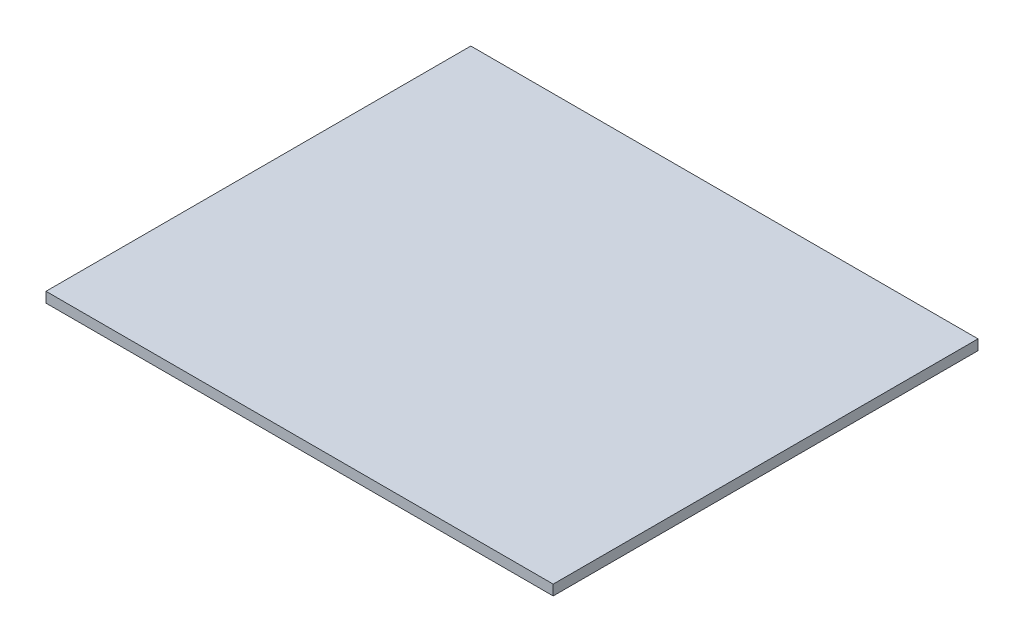
SolidWorks part; units mm, degrees
ref_plane "Front Plane" through (0, 0, 0) normal (0, 0, 1) x (1, 0, 0)
ref_plane "Top Plane" through (0, 0, 0) normal (0, 1, 0) x (1, 0, 0)
ref_plane "Right Plane" through (0, 0, 0) normal (1, 0, 0) x (0, 0, -1)
sketch "Sketch1" plane through (0, 0, 0) normal (0, 1, 0) x (1, 0, 0)
  line L1 (0, -523.875) -> (625.475, -523.875)
  line L2 (0, -523.875) -> (0, 0)
  line L3 (0, 0) -> (625.475, 0)
  line L4 (625.475, -523.875) -> (625.475, 0)
  line L5 (0, -523.875) -> (625.475, 0) construction
  line L6 (0, 0) -> (625.475, -523.875) construction
  point P0 (-2.6304, 18.4824)
  dimension "D1" = 625.475
  dimension "D2" = 523.875
extrude "Boss-Extrude1" add sketch "Sketch1" along normal blind 12.7
